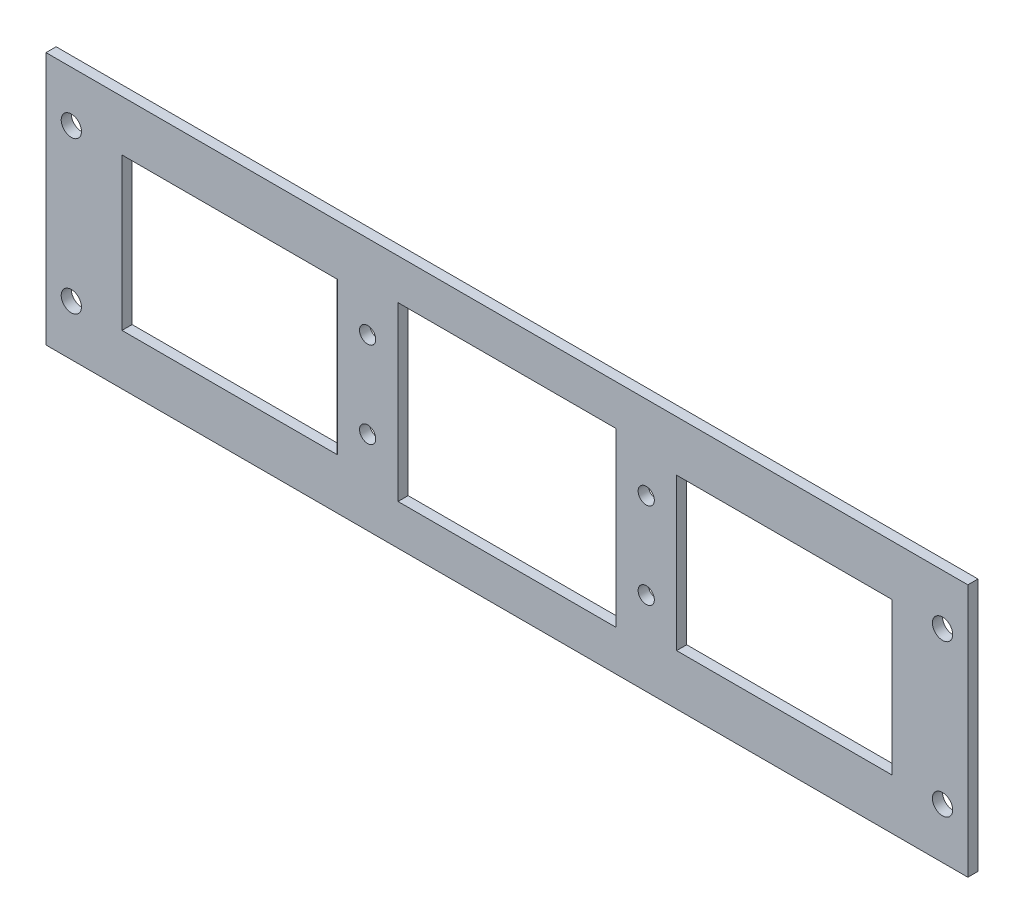
SolidWorks part; units mm, degrees
material "Thornel Mat VMA"
ref_plane "前视基准面" through (0, 0, 0) normal (0, 0, 1) x (1, 0, 0)
ref_plane "上视基准面" through (0, 0, 0) normal (0, 1, 0) x (1, 0, 0)
ref_plane "右视基准面" through (0, 0, 0) normal (1, 0, 0) x (0, 0, -1)
sketch "草图1" plane through (0, 0, 0) normal (0, 0, 1) x (1, 0, 0)
  line L0 (0, 34.936) -> (0, -27.1725) construction
  line L1 (-143.5263, 0) -> (187.6245, 0) construction
  line L2 (0, 0) -> (-154.281, 0) construction
  line L3 (-91, -25) -> (91, -25)
  line L4 (-91, -25) -> (-91, 25)
  line L5 (-91, 25) -> (91, 25)
  line L6 (91, -25) -> (91, 25)
  line L7 (-91, -25) -> (91, 25) construction
  line L8 (-91, 25) -> (91, -25) construction
  circle A0 centre (-86, 15) radius 2
  circle A1 centre (86, 15) radius 2
  circle A2 centre (-86, -15) radius 2
  circle A3 centre (86, -15) radius 2
  point P17 (0, 0)
  dimension "D1" = 4
  dimension "D2" = 30
  dimension "D3" = 172
  dimension "D4" = 10
  dimension "D5" = 10
  dimension "D6" = 5
extrude "凸台-拉伸1" add sketch "草图1" along normal blind 2
sketch "草图2" plane through (0, 0, 2) normal (0, 0, 1) x (1, 0, 0)
  line L0 (0, 40.3675) -> (0, -51.1457) construction
  line L1 (-128.7284, 0) -> (117.5435, 0) construction
  circle A0 centre (-27.5, 8.5) radius 1.6
  circle A1 centre (-27.5, -8.5) radius 1.6
  circle A2 centre (27.5, 8.5) radius 1.6
  circle A3 centre (27.5, -8.5) radius 1.6
  dimension "D1" = 17
  dimension "D2" = 3.2
  dimension "D3" = 55
extrude "切除-拉伸1" cut sketch "草图2" against normal through all
sketch "草图3" plane through (0, 0, 2) normal (0, 0, 1) x (1, 0, 0)
  line L0 (0, 33.2324) -> (0, -40.5704) construction
  line L1 (-21.5, 17) -> (21.5, 17)
  line L2 (-21.5, 17) -> (-21.5, -17)
  line L3 (-21.5, -17) -> (21.5, -17)
  line L4 (21.5, 17) -> (21.5, -17)
  line L5 (-21.5, 17) -> (21.5, -17) construction
  line L6 (-21.5, -17) -> (21.5, 17) construction
  line L7 (-91, 0) -> (91, 0) construction
  line L8 (-91, 25) -> (-91, -25) construction
  line L9 (91, -25) -> (91, 25) construction
  line L10 (91, 25) -> (-91, 25) construction
  line L13 (-76, 15) -> (-33.5, 15)
  line L14 (-76, 15) -> (-76, -15)
  line L15 (-76, -15) -> (-33.5, -15)
  line L16 (-33.5, 15) -> (-33.5, -15)
  line L17 (-76, 15) -> (-33.5, -15) construction
  line L18 (-76, -15) -> (-33.5, 15) construction
  line L19 (33.5, 15) -> (76, 15)
  line L20 (33.5, 15) -> (33.5, -15)
  line L21 (33.5, -15) -> (76, -15)
  line L22 (76, 15) -> (76, -15)
  line L23 (33.5, 15) -> (76, -15) construction
  line L24 (33.5, -15) -> (76, 15) construction
  circle A0 centre (-27.5, 8.5) radius 1.6 construction
  circle A1 centre (-86, -15) radius 2 construction
  point P0 (0, 0)
  point P16 (-54.75, 0)
  point P21 (54.75, 0)
  dimension "D1" = 8
  dimension "D2" = 6
  dimension "D3" = 10
  dimension "D4" = 10
  dimension "D5" = 6
extrude "切除-拉伸2" cut sketch "草图3" against normal through all
